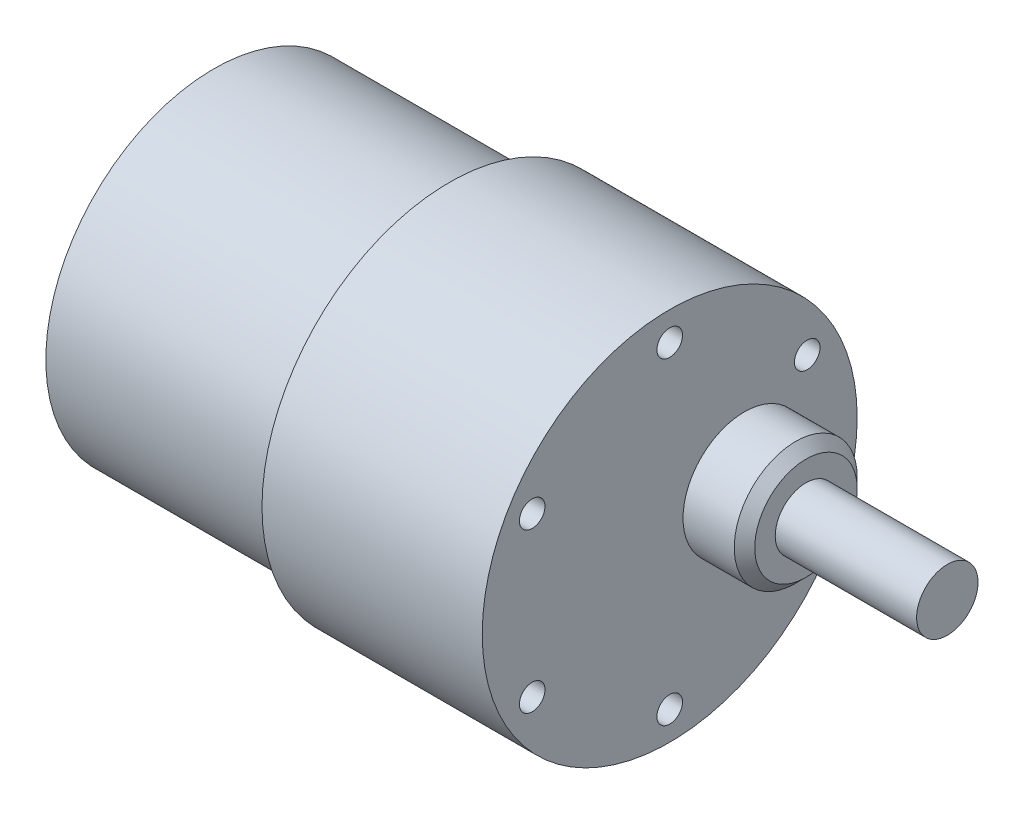
SolidWorks part; units mm, degrees
ref_plane "前视基准面" through (0, 0, 0) normal (0, 0, 1) x (1, 0, 0)
ref_plane "上视基准面" through (0, 0, 0) normal (0, 1, 0) x (1, 0, 0)
ref_plane "右视基准面" through (0, 0, 0) normal (1, 0, 0) x (0, 0, -1)
sketch "草图1" plane through (0, 0, 0) normal (1, 0, 0) x (0, 0, -1)
  circle A0 centre (0, 0) radius 16.4
  dimension "D1" = 32.8
extrude "凸台-拉伸1" add sketch "草图1" along normal blind 23
sketch "草图2" plane through (23, 0, 0) normal (1, 0, 0) x (0, 0, -1)
  circle A0 centre (0, 0) radius 18.3
  dimension "D1" = 36.6
extrude "凸台-拉伸2" add sketch "草图2" along normal blind 21.5
sketch "草图3" plane through (44.5, 0, 0) normal (1, 0, 0) x (0, 0, -1)
  circle A0 centre (7.3, 0) radius 6
  dimension "D1" = 12
  dimension "D2" = 7.3
extrude "凸台-拉伸3" add sketch "草图3" along normal blind 6
sketch "草图4" plane through (50.5, 0, 0) normal (1, 0, 0) x (0, 0, -1)
  circle A0 centre (7.3, 0) radius 3
  dimension "D1" = 6
extrude "凸台-拉伸4" add sketch "草图4" along normal blind 13.8
sketch "草图5" plane through (44.5, 0, 0) normal (1, 0, 0) x (0, 0, -1)
  circle A0 centre (0, 15.5) radius 2.1265
  dimension "D1" = 4.253
  dimension "D2" = 15.5
hole_wizard "M3 螺纹孔1" positions "草图6" profile "草图7" tap size "M3" standard "IS"
sketch "草图6" plane through (44.5, 0, 0) normal (1, 0, 0) x (0, 0, -1)
  point P0 (0, 15.5)
sketch "草图7" plane through (44.5, 15.5, 0) normal (0, 1, 0) x (0, 0, -1)
  line L0 (0, 0) -> (0, 5.7511)
  line L1 (0, 5.7511) -> (1.25, 5)
  line L2 (1.25, 5) -> (1.25, 0)
  line L5 (1.25, 0) -> (0, 0)
  line L10 (0, 5.7511) -> (-1.25, 5) construction
  line L11 (0, -6.35) -> (0, 107.95) construction
  dimension "螺纹孔钻头直径" = 2.5
  dimension "螺纹孔钻头深度" = 5
  dimension "导头角度" = 118
cosmetic thread "孔螺蚊线1" parameters "D1"=5, "D2"=3
pattern_circular "阵列(圆周)1" count 6 over 360 about axis through (0, 0, 0) along (1, 0, 0) of "M3 螺纹孔1"
cosmetic thread "孔螺蚊线2" parameters "D1"=5, "D2"=3
cosmetic thread "孔螺蚊线3" parameters "D1"=5, "D2"=3
cosmetic thread "孔螺蚊线4" parameters "D1"=5, "D2"=3
cosmetic thread "孔螺蚊线5" parameters "D1"=5, "D2"=3
cosmetic thread "孔螺蚊线6" parameters "D1"=5, "D2"=3
chamfer "倒角1" distance 1 angle 45 1 edges at (50.5, 0, -13.3)
